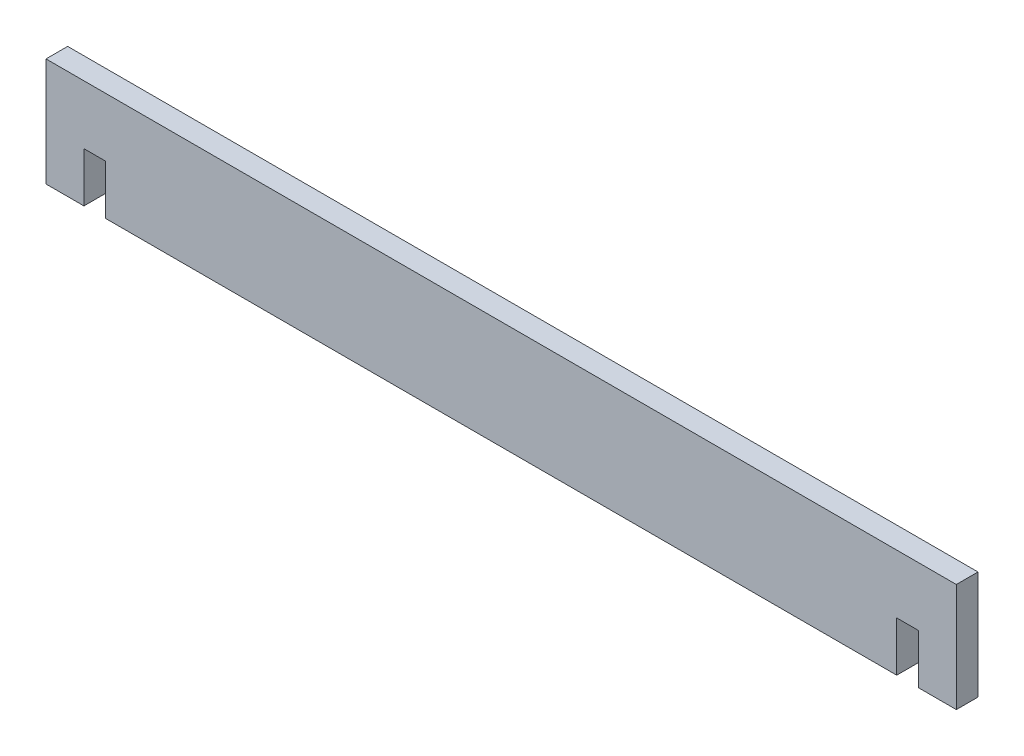
SolidWorks part; units mm, degrees
ref_plane "Front Plane" through (0, 0, 0) normal (0, 0, 1) x (1, 0, 0)
ref_plane "Top Plane" through (0, 0, 0) normal (0, 1, 0) x (1, 0, 0)
ref_plane "Right Plane" through (0, 0, 0) normal (1, 0, 0) x (0, 0, -1)
sketch "Sketch1" plane through (0, 0, 0) normal (0, 0, 1) x (1, 0, 0)
  line L0 (-192.5, -22.8893) -> (-192.5, 0)
  line L1 (-210, 27.1107) -> (210, 27.1107)
  line L3 (-210, -22.8893) -> (-192.5, -22.8893)
  line L5 (-192.5, 0) -> (-182.5, 0)
  line L6 (-182.5, 0) -> (-182.5, -22.8893)
  line L7 (182.5, -22.8893) -> (182.5, 0)
  line L8 (182.5, 0) -> (192.5, 0)
  line L9 (192.5, 0) -> (192.5, -22.8893)
  line L10 (-182.5, -22.8893) -> (182.5, -22.8893)
  line L11 (192.5, -22.8893) -> (210, -22.8893)
  line L12 (-210, 27.1107) -> (-210, -22.8893)
  line L13 (210, 27.1107) -> (210, -22.8893)
  point P3 (0, 0)
  point P14 (-210, -22.8893)
  point P15 (0, 0)
  dimension "D1" = 420
  dimension "D2" = 10
  dimension "D3" = 10
  dimension "D4" = 365
  dimension "D5" = 210
  dimension "D6" = 182.5
  dimension "D7" = 50
extrude "Boss-Extrude1" add sketch "Sketch1" along normal blind 10
